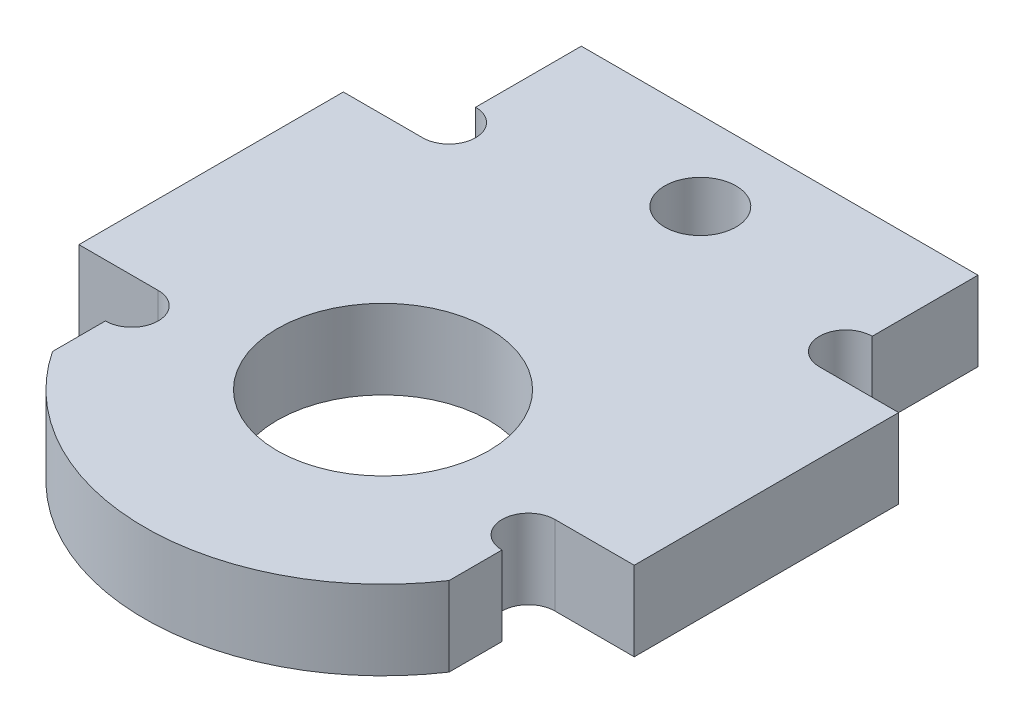
SolidWorks part; units mm, degrees
material "碳纤维"
ref_plane "前视基准面" through (0, 0, 0) normal (0, 0, 1) x (1, 0, 0)
ref_plane "上视基准面" through (0, 0, 0) normal (0, 1, 0) x (1, 0, 0)
ref_plane "右视基准面" through (0, 0, 0) normal (1, 0, 0) x (0, 0, -1)
sketch "草图1" plane through (0, 0, 0) normal (0, 1, 0) x (1, 0, 0)
  line L2 (-7.5, 0) -> (-7.5, 5)
  line L3 (-7.5, 5) -> (7.5, 5)
  line L4 (7.5, 0) -> (7.5, 5)
  line L5 (0, 5) -> (0, -7.5) construction
  line L6 (-7.5, 0) -> (7.5, 0) construction
  line L7 (7.5, 0) -> (7.5, -5)
  line L9 (-7.5, -5) -> (-7.5, 0)
  circle A0 centre (0, 0) radius 4
  arc A3 (-7.5, -5) -> (7.5, -5) centre (0, 0) ccw
  point P0 (0, 0)
  dimension "D1" = 8
  dimension "D2" = 5
  dimension "D3" = 5
  dimension "D5" = 15
extrude "凸台-拉伸1" add sketch "草图1" along normal blind 3
sketch "草图3" plane through (0, 3, 0) normal (0, 1, 0) x (1, 0, 0)
  line L0 (7.5, -5) -> (7.5, 5) construction
  line L1 (-7.5, 5) -> (7.5, 5)
  line L2 (-7.5, 5) -> (-7.5, 15)
  line L3 (-7.5, 15) -> (7.5, 15)
  line L4 (7.5, 5) -> (7.5, 15)
  circle A0 centre (0, 0) radius 4 construction
  dimension "D1" = 15
extrude "凸台-拉伸3" add sketch "草图3" against normal up to surface (3 mm away) up to face at (0, 0, 1.0035)
sketch "草图2" plane through (0, 3, 0) normal (0, 1, 0) x (1, 0, 0)
  line L5 (-7.5, 15) -> (7.5, 15) construction
  line L6 (0, 0) -> (0, -4) construction
  line L8 (10.5, 9) -> (10.5, -1)
  line L9 (7.5, 9) -> (10.5, 9)
  line L11 (7.5, -5) -> (7.5, 15) construction
  line L12 (7.5, 9) -> (7.5, -1)
  line L20 (10.5, -1) -> (7.5, -1)
  line L21 (7.5, -5) -> (7.5, 15) construction
  line L22 (-7.5, 9) -> (-10.5, 9)
  line L23 (-10.5, 9) -> (-10.5, -1)
  line L24 (-10.5, -1) -> (-7.5, -1)
  line L25 (-7.5, 9) -> (-7.5, -1)
  circle A0 centre (0, 0) radius 4 construction
  dimension "D1" = 3
  dimension "D2" = 10
  dimension "D3" = 6
extrude "凸台-拉伸4" add sketch "草图2" against normal up to surface (3 mm away) up to face at (0, 0, -3.9965)
sketch "草图4" plane through (0, 0, 0) normal (0, -1, 0) x (1, 0, 0)
  line L0 (7.5, -9) -> (7.5, -15) construction
  line L1 (-10.5, -4) -> (0, -4) construction
  line L2 (-10.5, 1) -> (-10.5, -9) construction
  line L3 (0, -4) -> (0, -0.2783) construction
  circle A0 centre (7.5, -10) radius 1
  circle A2 centre (7.5, 2) radius 1
  circle A3 centre (-7.5, 2) radius 1
  circle A4 centre (-7.5, -10) radius 1
  dimension "D1" = 2
extrude "切除-拉伸1" cut sketch "草图4" against normal through all
sketch "草图5" plane through (0, 0, 0) normal (0, -1, 0) x (1, 0, 0)
  line L0 (-7.5, -15) -> (7.5, -15) construction
  line L1 (0, 0) -> (0, -12) construction
  circle A0 centre (0, -12) radius 1.35
  dimension "D1" = 2.7
  dimension "D2" = 3
extrude "切除-拉伸2" cut sketch "草图5" against normal through all
